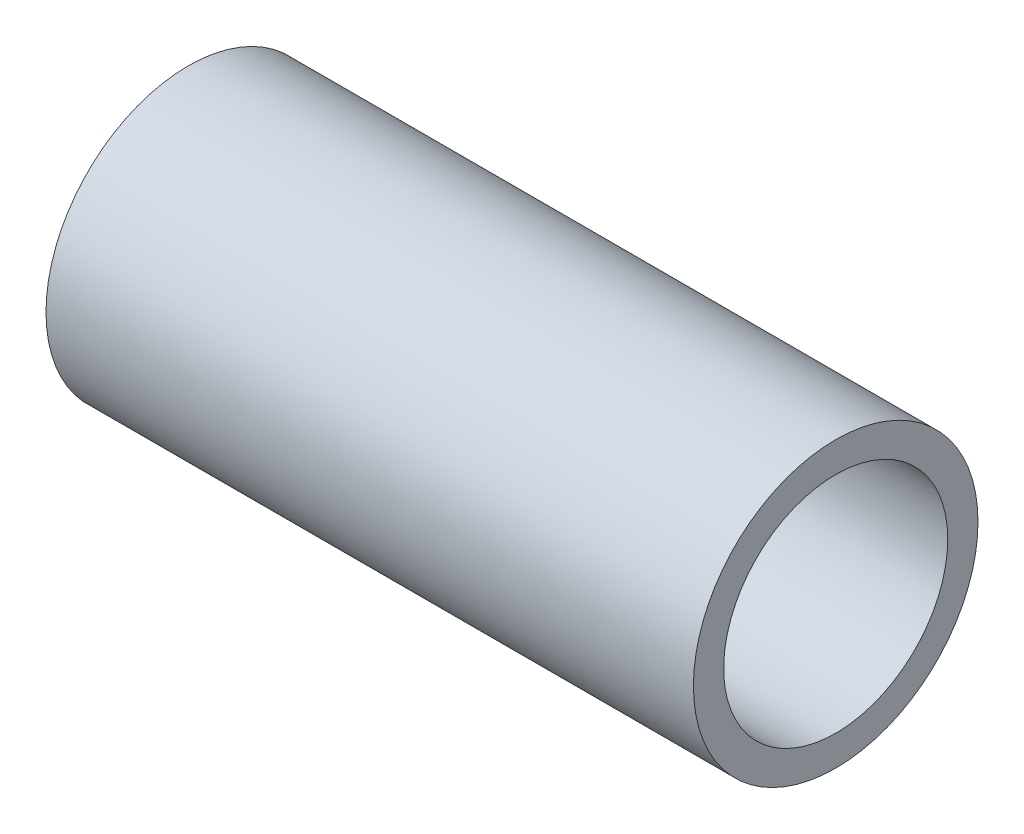
SolidWorks part; units mm, degrees
ref_plane "Front Plane" through (0, 0, 0) normal (0, 0, 1) x (1, 0, 0)
ref_plane "Top Plane" through (0, 0, 0) normal (0, 1, 0) x (1, 0, 0)
ref_plane "Right Plane" through (0, 0, 0) normal (1, 0, 0) x (0, 0, -1)
sketch "Sketch1" plane through (0, 0, 0) normal (1, 0, 0) x (0, 0, -1)
  circle A0 centre (0, 0) radius 6.35
  circle A1 centre (0, 0) radius 10.16
extrude "Boss-Extrude2" add sketch "Sketch1" along normal blind 20.828
sketch "Sketch2" plane through (0, 0, 0) normal (-1, 0, 0) x (0, 0, 1)
  circle A0 centre (0, 0) radius 8.001
  circle A1 centre (0, 0) radius 10.16
extrude "Boss-Extrude3" add sketch "Sketch2" along normal blind 12.7
sketch "Sketch3" plane through (20.828, 0, 0) normal (1, 0, 0) x (0, 0, -1)
  circle A0 centre (0, 0) radius 8.001
  circle A1 centre (0, 0) radius 10.16
extrude "Boss-Extrude4" add sketch "Sketch3" along normal blind 12.7
